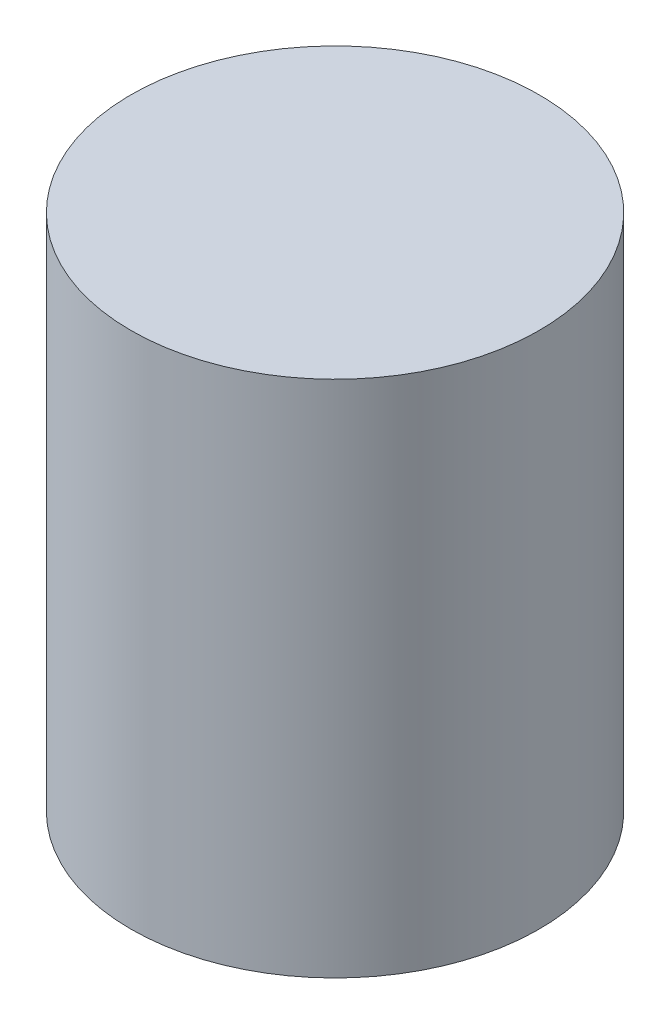
SolidWorks part; units mm, degrees
material "1023 Carbon Steel Sheet (SS)"
ref_plane "Front Plane" through (0, 0, 0) normal (0, 0, 1) x (1, 0, 0)
ref_plane "Top Plane" through (0, 0, 0) normal (0, 1, 0) x (1, 0, 0)
ref_plane "Right Plane" through (0, 0, 0) normal (1, 0, 0) x (0, 0, -1)
sketch "Sketch1" plane through (0, 0, 0) normal (0, 1, 0) x (1, 0, 0)
  circle A0 centre (0, 0) radius 25
  dimension "D1" = 50
extrude "Boss-Extrude1" add sketch "Sketch1" along normal blind 63.5
sketch "Sketch2" plane through (0, 63.5, 0) normal (0, 1, 0) x (1, 0, 0)
  line L0 (0, 25) -> (0, -25) construction
  circle A1 centre (0, 0) radius 25 construction
